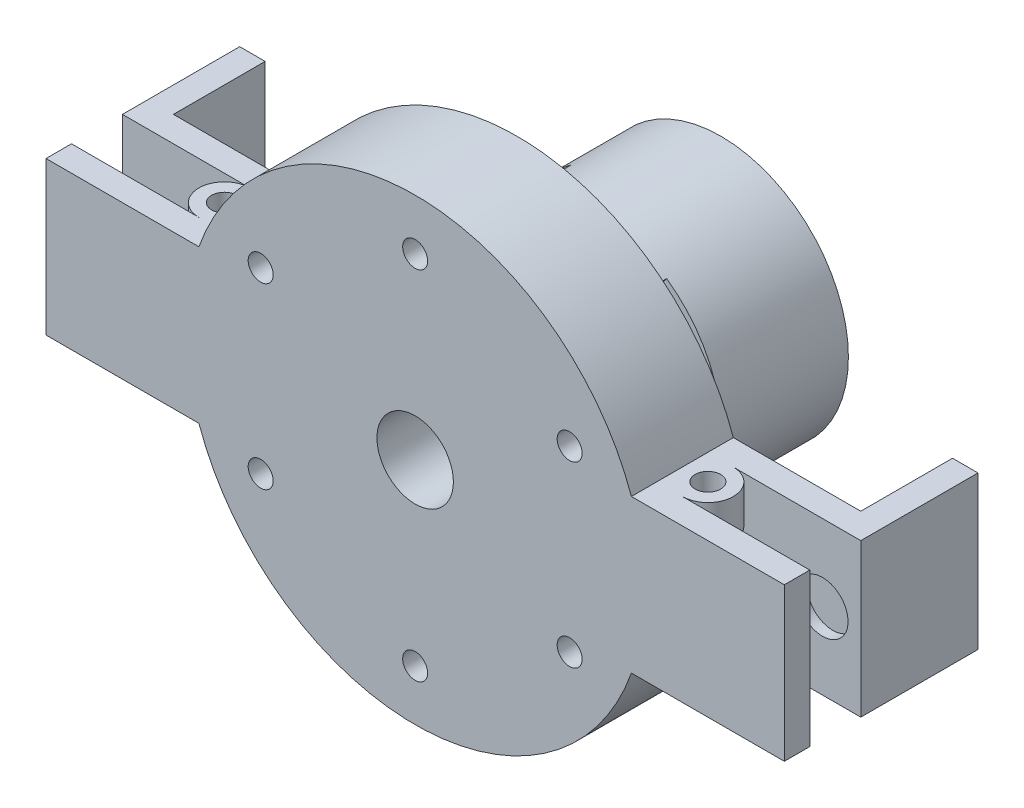
SolidWorks part; units mm, degrees
ref_plane "Ön Düzlem" through (0, 0, 0) normal (0, 0, 1) x (1, 0, 0)
ref_plane "Üst Düzlem" through (0, 0, 0) normal (0, 1, 0) x (1, 0, 0)
ref_plane "Sağ Düzlem" through (0, 0, 0) normal (1, 0, 0) x (0, 0, -1)
sketch "Çizim1" plane through (0, 0, 0) normal (0, 0, 1) x (1, 0, 0)
  circle A1 centre (0, 0) radius 45
  circle A2 centre (0, 35) radius 2.45
  circle A3 centre (30.3109, 17.5) radius 2.45
  circle A4 centre (30.3109, -17.5) radius 2.45
  circle A5 centre (0, -35) radius 2.45
  circle A6 centre (-30.3109, -17.5) radius 2.45
  circle A7 centre (-30.3109, 17.5) radius 2.45
  point P19 (0, 0)
  dimension "D2" = 90
  dimension "D3" = 4.9
  dimension "D4" = 6
extrude "Yükseklik-Ekstrüzyon1" add sketch "Çizim1" along normal blind 20
sketch "Çizim2" plane through (0, 0, 0) normal (0, 0, -1) x (-1, 0, 0)
  circle A0 centre (0, 0) radius 25
  dimension "D1" = 50
extrude "Yükseklik-Ekstrüzyon2" add sketch "Çizim2" along normal blind 40
sketch "Çizim3" plane through (0, 0, 20) normal (0, 0, 1) x (1, 0, 0)
  line L0 (-59.8123, 0) -> (54.7981, 0) construction
  line L1 (42.4264, -15) -> (72.4264, -15)
  line L2 (72.4264, -15) -> (72.4264, 15)
  line L3 (72.4264, 15) -> (42.4264, 15)
  line L4 (0, 83.045) -> (0, -86.5383) construction
  line L5 (-42.4264, -15) -> (-72.4264, -15)
  line L6 (-72.4264, -15) -> (-72.4264, 15)
  line L7 (-72.4264, 15) -> (-42.4264, 15)
  circle A0 centre (0, 0) radius 45 construction
  arc A1 (-42.4264, -15) -> (-42.4264, 15) centre (0, 0) cw
  circle A2 centre (0, 0) radius 45
  arc A3 (42.4264, -15) -> (42.4264, 15) centre (0, 0) ccw
  dimension "D1" = 15
  dimension "D2" = 15
  dimension "D3" = 30
  dimension "D4" = 0
extrude "Yükseklik-Ekstrüzyon3" add sketch "Çizim3" against normal blind 20
sketch "Çizim4" plane through (0, 15, 0) normal (0, 1, 0) x (1, 0, 0)
  line L0 (72.4264, 0) -> (72.4264, -20) construction
  line L1 (72.4264, -5) -> (47.4264, -5)
  line L3 (72.4264, -15) -> (47.4264, -15)
  line L5 (0, 58.7502) -> (0, -65.662) construction
  line L6 (72.4264, 0) -> (42.4264, 0) construction
  line L7 (72.4264, -20) -> (42.4264, -20) construction
  line L8 (72.4264, -15) -> (72.4264, -5)
  line L9 (-72.4264, -15) -> (-47.4264, -15)
  line L10 (-72.4264, -5) -> (-47.4264, -5)
  line L11 (-72.4264, -15) -> (-72.4264, -5)
  arc A0 (47.4264, -15) -> (47.4264, -5) centre (47.4264, -10) ccw
  circle A1 centre (47.4264, -10) radius 2.5
  arc A2 (-47.4264, -15) -> (-47.4264, -5) centre (-47.4264, -10) cw
  circle A3 centre (-47.4264, -10) radius 2.5
  dimension "D3" = 10
  dimension "D5" = 5
  dimension "D1" = 5
  dimension "D2" = 5
extrude "Kes-Ekstrüzyon1" cut sketch "Çizim4" against normal blind 30
sketch "Çizim5" plane through (72.4264, 0, 0) normal (1, 0, 0) x (0, 0, -1)
  line L1 (-15, -7.5) -> (-5, -7.5)
  line L3 (-15, 7.5) -> (-5, 7.5)
  line L6 (0, 15) -> (-20, 15) construction
  line L7 (-15, -15) -> (-5, -15) construction
  line L8 (-15, -7.5) -> (-15, 7.5)
  line L9 (-15, -15) -> (-15, 15) construction
  line L10 (-5, 7.5) -> (-5, -7.5)
  line L11 (-5, -15) -> (-5, 15) construction
  dimension "D1" = 7.5
  dimension "D2" = 7.5
extrude "Kes-Ekstrüzyon3" cut sketch "Çizim5" against normal blind 30
sketch "Çizim8" plane through (0, 0, 5) normal (0, 0, 1) x (1, 0, 0)
  line L0 (0, 0) -> (79.1851, 0) construction
  line L1 (72.4264, -15) -> (72.4264, 15) construction
  line L2 (0, 51.6705) -> (0, -59.9853) construction
  circle A0 centre (64.9264, 0) radius 5
  circle A1 centre (-64.9264, 0) radius 5
  dimension "D1" = 10
  dimension "D2" = 7.5
extrude "Kes-Ekstrüzyon4" cut sketch "Çizim8" against normal blind 2
sketch "Çizim10" plane through (0, 0, 20) normal (0, 0, 1) x (1, 0, 0)
  circle A0 centre (0, 0) radius 7.5
  dimension "D1" = 15
extrude "Kes-Ekstrüzyon5" cut sketch "Çizim10" against normal blind 25
sketch "Çizim12" plane through (0, 15, 0) normal (0, 1, 0) x (1, 0, 0)
  line L0 (72.4264, 0) -> (72.4264, 18)
  line L1 (72.4264, 18) -> (67.4264, 18)
  line L2 (67.4264, 18) -> (67.4264, 0)
  line L3 (72.4264, 0) -> (42.4264, 0) construction
  line L4 (67.4264, 0) -> (72.4264, 0)
  line L5 (0, 62.0416) -> (0, -66.3203) construction
  line L6 (-67.4264, 18) -> (-67.4264, 0)
  line L7 (-72.4264, 18) -> (-67.4264, 18)
  line L8 (-72.4264, 0) -> (-72.4264, 18)
  line L9 (-67.4264, 0) -> (-72.4264, 0)
  dimension "D1" = 18
  dimension "D2" = 5
extrude "Yükseklik-Ekstrüzyon4" add sketch "Çizim12" against normal blind 30
sketch "Çizim14" plane through (-72.4264, 0, 0) normal (-1, 0, 0) x (0, 0, 1)
  line L0 (5, -15) -> (5, 15) construction
  line L1 (5, 7.5) -> (15, 7.5)
  line L2 (5, 7.5) -> (5, -7.5)
  line L3 (5, -7.5) -> (15, -7.5)
  line L4 (15, 7.5) -> (15, -7.5)
  line L5 (15, -15) -> (15, 15) construction
  line L6 (0, 15) -> (20, 15) construction
  line L7 (0, -15) -> (20, -15) construction
  dimension "D1" = 7.5
  dimension "D2" = 7.5
extrude "Kes-Ekstrüzyon6" cut sketch "Çizim14" against normal blind 30
sketch "Çizim16" plane through (0, 0, -40) normal (0, 0, -1) x (-1, 0, 0)
  circle A0 centre (0, 0) radius 15
  dimension "D1" = 30
extrude "Kes-Ekstrüzyon8" cut sketch "Çizim16" against normal blind 35
sketch "Çizim17" plane through (0, 0, -40) normal (0, 0, -1) x (-1, 0, 0)
  line L0 (-87.8993, 0) -> (84.4843, 0) construction
  line L1 (0, 53.1553) -> (0, 25) construction
  line L2 (-25, 0) -> (-15, 0)
  line L4 (0, 0) -> (-33.2864, 47.5379) construction
  line L5 (-8.6036, 12.2873) -> (-14.3394, 20.4788)
  line L6 (0, 15) -> (0, -54.6401) construction
  arc A0 (-8.6036, 12.2873) -> (-15, 0) centre (0, 0) ccw
  arc A1 (-14.3394, 20.4788) -> (-25, 0) centre (0, 0) ccw
  dimension "D1" = 35
extrude "Kes-Ekstrüzyon9" cut sketch "Çizim17" against normal blind 10 from offset 25 offset against normal yes
sketch "Çizim18" plane through (0, 0, -40) normal (0, 0, -1) x (-1, 0, 0)
  line L0 (0, 54.0462) -> (0, -54.4916) construction
  line L1 (-93.393, 0) -> (94.1354, 0) construction
  line L2 (0, 0) -> (33.7495, 48.1993) construction
  line L3 (8.6036, 12.2873) -> (14.3394, 20.4788)
  line L4 (15, 0) -> (25, 0)
  arc A0 (15, 0) -> (8.6036, 12.2873) centre (0, 0) ccw
  arc A1 (25, 0) -> (14.3394, 20.4788) centre (0, 0) ccw
  dimension "D1" = 35
extrude "Kes-Ekstrüzyon10" cut sketch "Çizim18" against normal blind 10 from offset 15 offset against normal yes
